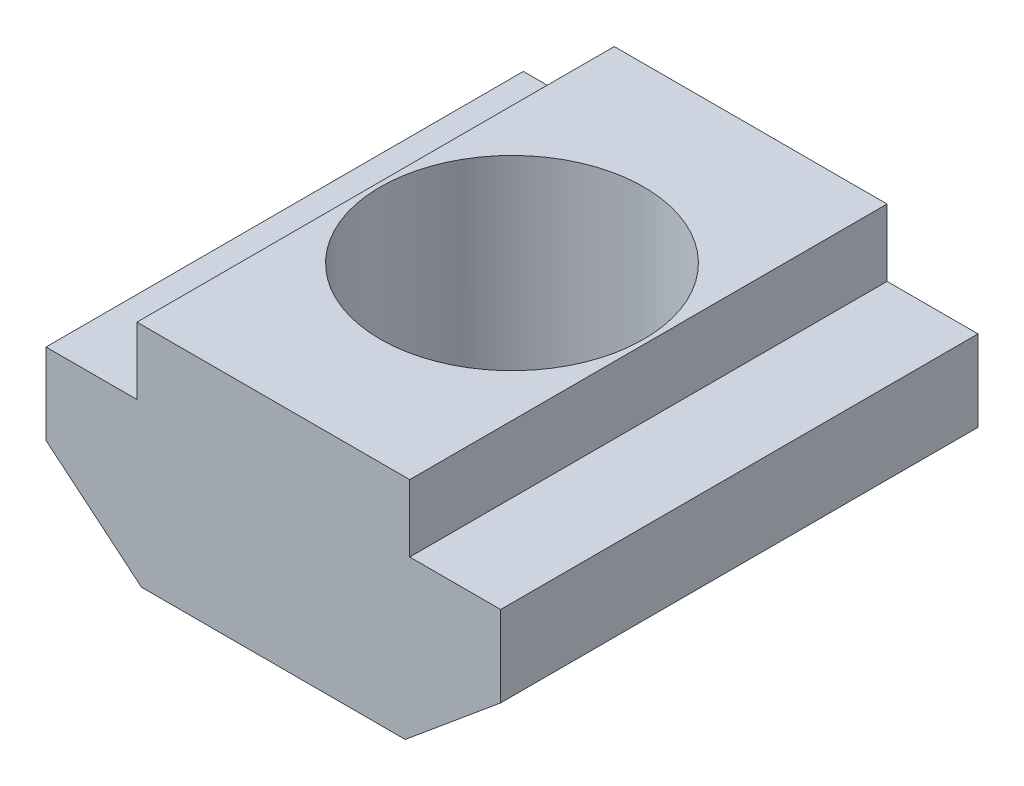
SolidWorks part; units mm, degrees
ref_plane "Front Plane" through (0, 0, 0) normal (0, 0, 1) x (1, 0, 0)
ref_plane "Top Plane" through (0, 0, 0) normal (0, 1, 0) x (1, 0, 0)
ref_plane "Right Plane" through (0, 0, 0) normal (1, 0, 0) x (0, 0, -1)
sketch "Sketch1" plane through (0, 0, 0) normal (0, 0, 1) x (1, 0, 0)
  line L0 (-2.9, -2.5) -> (2.9, -2.5)
  line L1 (-5, 2.5) -> (5, 2.5) construction
  line L2 (-5, 2.5) -> (-5, -2.5) construction
  line L3 (-5, -2.5) -> (5, -2.5) construction
  line L4 (5, 2.5) -> (5, -2.5) construction
  line L5 (-5, 2.5) -> (5, -2.5) construction
  line L6 (-5, -2.5) -> (5, 2.5) construction
  line L7 (-2.9, -2.5) -> (-5, -0.754)
  line L8 (-5, -0.754) -> (-5, 1.026)
  line L9 (0, 2.5) -> (0, -2.5) construction
  line L10 (-5, 1.026) -> (-3, 1.026)
  line L11 (-3, 1.026) -> (-3, 2.5)
  line L12 (2.9, -2.5) -> (5, -0.754)
  line L13 (5, -0.754) -> (5, 1.026)
  line L14 (3, 1.026) -> (3, 2.5)
  line L15 (5, 1.026) -> (3, 1.026)
  line L16 (-3, 2.5) -> (3, 2.5)
  point P0 (0, 0)
  point P9 (0, -2.5)
  dimension "D1" = 5
  dimension "D2" = 10
  dimension "D3" = 5.8
  dimension "D4" = 1.78
  dimension "D5" = 3
extrude "Boss-Extrude1" add sketch "Sketch1" along normal blind 10.5
sketch "Sketch2" plane through (0, 2.5, 0) normal (0, 1, 0) x (1, 0, 0)
  circle A0 centre (0, -5.25) radius 2.9
  dimension "D1" = 5.8
extrude "Cut-Extrude1" cut sketch "Sketch2" against normal through all
